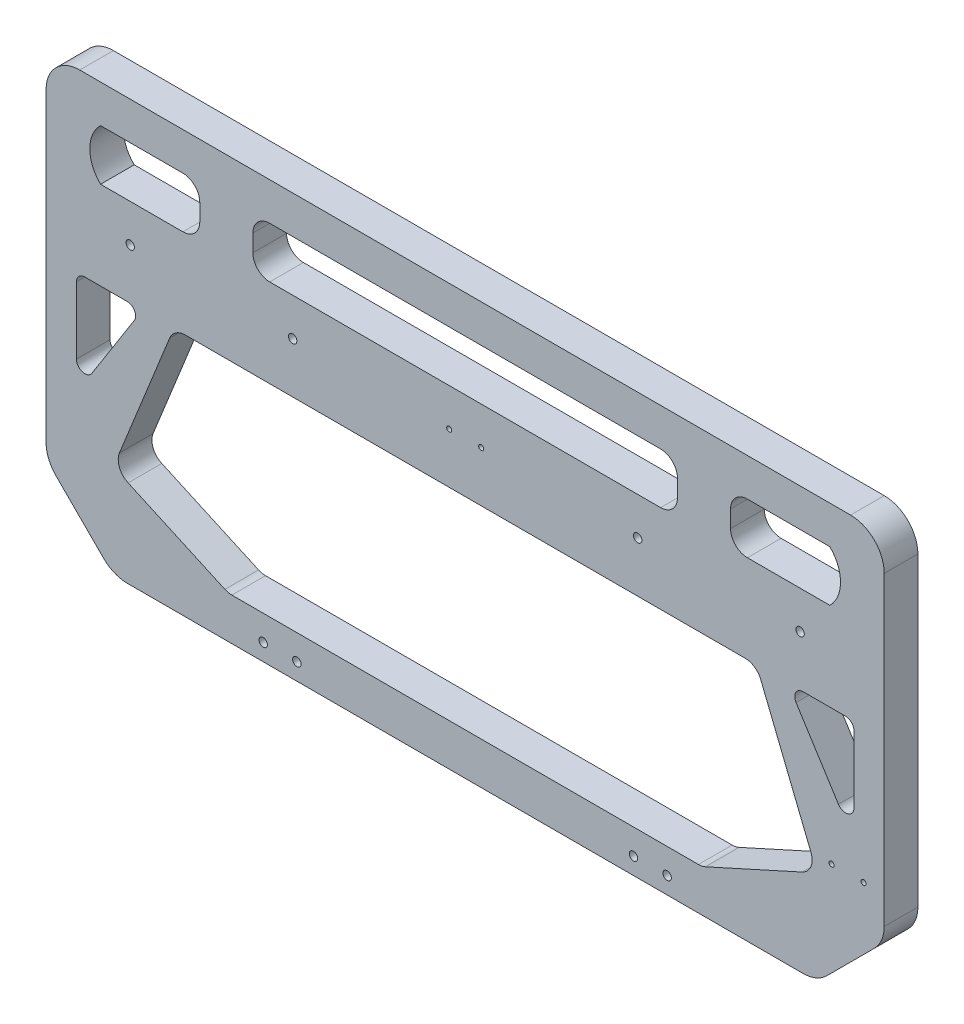
SolidWorks part; units mm, degrees
ref_plane "Ön Düzlem" through (0, 0, 0) normal (0, 0, 1) x (1, 0, 0)
ref_plane "Üst Düzlem" through (0, 0, 0) normal (0, 1, 0) x (1, 0, 0)
ref_plane "Sağ Düzlem" through (0, 0, 0) normal (1, 0, 0) x (0, 0, -1)
sketch "Sketch1" plane through (0, 0, 0) normal (0, 0, 1) x (1, 0, 0)
  line L0 (0, 125) -> (0, -125) construction
  line L1 (-200.7157, -125) -> (200.7157, -125)
  line L2 (-249, -76.7157) -> (-249, 105)
  line L3 (-229, 125) -> (229, 125)
  line L4 (249, -76.7157) -> (249, 105)
  line L5 (-249, 50) -> (249, 50) construction
  line L6 (116.1318, 102.5635) -> (-116.1318, 102.5635)
  line L7 (-126.1318, 92.5635) -> (-126.1318, 82.3895)
  line L8 (-116.1318, 72.3895) -> (116.1318, 72.3895)
  line L9 (-216.6539, 102.5635) -> (-167.6985, 102.5635)
  line L13 (-157.6985, 92.5635) -> (-157.6985, 82.3895)
  line L14 (-167.6985, 72.3895) -> (-216.6539, 72.3895)
  line L15 (166.3188, 20) -> (-166.3188, 20)
  line L16 (-175.5934, 13.7393) -> (-205.414, -60.224)
  line L17 (-200.2635, -73.0733) -> (-142.7494, -99.11)
  line L18 (-138.6253, -100) -> (138.6253, -100)
  line L19 (-231, 15) -> (-231, -24.7569)
  line L20 (-221.7756, -27.4317) -> (-196.6027, 12.3252)
  line L21 (-200.8271, 20) -> (-226, 20)
  line L22 (200.2635, -73.0733) -> (142.7494, -99.11)
  line L23 (175.5934, 13.7393) -> (205.414, -60.224)
  line L24 (126.1318, 92.5635) -> (126.1318, 82.3895)
  line L25 (221.7756, -27.4317) -> (196.6027, 12.3252)
  line L26 (231, 15) -> (231, -24.7569)
  line L27 (200.8271, 20) -> (226, 20)
  line L28 (157.6985, 92.5635) -> (157.6985, 82.3895)
  line L29 (216.6539, 102.5635) -> (167.6985, 102.5635)
  line L30 (167.6985, 72.3895) -> (216.6539, 72.3895)
  line L31 (-243.1421, -90.8579) -> (-214.8579, -119.1421)
  line L32 (214.8579, -119.1421) -> (243.1421, -90.8579)
  circle A0 centre (-199, 50) radius 2.5
  circle A1 centre (-102.5, 50) radius 2.5
  circle A2 centre (102.5, 50) radius 2.5
  circle A3 centre (199, 50) radius 2.5
  circle A4 centre (-9.5, 50) radius 1.5
  circle A5 centre (9.5, 50) radius 1.5
  arc A6 (-216.6539, 102.5635) -> (-216.6539, 72.3895) centre (-202.0042, 87.4765) ccw
  arc A7 (-167.6985, 102.5635) -> (-157.6985, 92.5635) centre (-167.6985, 92.5635) cw
  arc A8 (-157.6985, 82.3895) -> (-167.6985, 72.3895) centre (-167.6985, 82.3895) cw
  arc A9 (-116.1318, 102.5635) -> (-126.1318, 92.5635) centre (-116.1318, 92.5635) ccw
  arc A10 (-126.1318, 82.3895) -> (-116.1318, 72.3895) centre (-116.1318, 82.3895) ccw
  arc A11 (-231, -24.7569) -> (-221.7756, -27.4317) centre (-226, -24.7569) ccw
  arc A12 (-231, 15) -> (-226, 20) centre (-226, 15) cw
  arc A13 (-196.6027, 12.3252) -> (-200.8271, 20) centre (-200.8271, 15) ccw
  arc A14 (-166.3188, 20) -> (-175.5934, 13.7393) centre (-166.3188, 10) ccw
  arc A15 (-142.7494, -99.11) -> (-138.6253, -100) centre (-138.6253, -90) ccw
  arc A16 (-205.414, -60.224) -> (-200.2635, -73.0733) centre (-196.1394, -63.9633) ccw
  arc A17 (142.7494, -99.11) -> (138.6253, -100) centre (138.6253, -90) cw
  arc A18 (205.414, -60.224) -> (200.2635, -73.0733) centre (196.1394, -63.9633) cw
  arc A19 (166.3188, 20) -> (175.5934, 13.7393) centre (166.3188, 10) cw
  arc A20 (116.1318, 102.5635) -> (126.1318, 92.5635) centre (116.1318, 92.5635) cw
  arc A21 (126.1318, 82.3895) -> (116.1318, 72.3895) centre (116.1318, 82.3895) cw
  arc A22 (231, -24.7569) -> (221.7756, -27.4317) centre (226, -24.7569) cw
  arc A23 (231, 15) -> (226, 20) centre (226, 15) ccw
  arc A24 (196.6027, 12.3252) -> (200.8271, 20) centre (200.8271, 15) cw
  arc A25 (167.6985, 102.5635) -> (157.6985, 92.5635) centre (167.6985, 92.5635) ccw
  arc A26 (216.6539, 102.5635) -> (216.6539, 72.3895) centre (202.0042, 87.4765) cw
  arc A27 (157.6985, 82.3895) -> (167.6985, 72.3895) centre (167.6985, 82.3895) ccw
  arc A28 (229, 125) -> (249, 105) centre (229, 105) cw
  arc A29 (-249, 105) -> (-229, 125) centre (-229, 105) cw
  arc A30 (-243.1421, -90.8579) -> (-249, -76.7157) centre (-229, -76.7157) cw
  arc A31 (-214.8579, -119.1421) -> (-200.7157, -125) centre (-200.7157, -105) ccw
  arc A32 (214.8579, -119.1421) -> (200.7157, -125) centre (200.7157, -105) cw
  arc A33 (243.1421, -90.8579) -> (249, -76.7157) centre (229, -76.7157) ccw
  point P0 (0, 0)
  point P2 (-249, -125)
  point P4 (249, -125)
  point P59 (-209, -69.1183)
  point P63 (0, -100)
  point P69 (0, 20)
  point P73 (0, 102.5635)
  point P75 (0, 72.3895)
  point P99 (249, 125)
  point P104 (-249, -85)
  point P107 (-209, -125)
  point P110 (209, -125)
  point P113 (249, -85)
  dimension "D3" = 5
  dimension "D4" = 5
  dimension "D8" = 3
  dimension "D10" = 10
  dimension "D11" = 10
  dimension "D16" = 5
  dimension "D17" = 10
  dimension "D18" = 20
  dimension "D19" = 20
  dimension "D1" = 250
  dimension "D2" = 498
  dimension "D5" = 50
  dimension "D6" = 102.5
  dimension "D7" = 75
  dimension "D9" = 9.5
  dimension "D12" = 25
  dimension "D13" = 30
  dimension "D14" = 40
  dimension "D15" = 18
extrude "Boss-Extrude1" add sketch "Sketch1" along normal blind 20
sketch "Sketch3" plane through (0, 0, 20) normal (0, 0, 1) x (1, 0, 0)
  line L0 (0, 0) -> (0, -125) construction
  line L1 (-200.7157, -125) -> (200.7157, -125) construction
  line L3 (-74.5418, -125) -> (-74.5418, -105) construction
  line L4 (-74.5418, -115) -> (-10.3726, -115) construction
  circle A0 centre (-100, -115) radius 2.5
  circle A1 centre (-120, -115) radius 2.5
  circle A2 centre (100, -115) radius 2.5
  circle A3 centre (120, -115) radius 2.5
  dimension "D2" = 5
  dimension "D3" = 5
  dimension "D1" = 20
  dimension "D4" = 100
  dimension "D5" = 20
extrude "Cut-Extrude1" cut sketch "Sketch3" against normal up to surface (20 mm away) up to face at (196.5, 50, 0)
sketch "Sketch4" plane through (0, 0, 20) normal (0, 0, 1) x (1, 0, 0)
  line L0 (205.414, -60.224) -> (249, -60.224) construction
  line L1 (249, -76.7157) -> (249, 105) construction
  circle A0 centre (236.707, -60.224) radius 1.5
  circle A1 centre (217.707, -60.224) radius 1.5
  point P9 (227.207, -60.224)
  dimension "D1" = 3
  dimension "D2" = 3
  dimension "D3" = 9.5
  dimension "D4" = 19
extrude "Cut-Extrude2" cut sketch "Sketch4" against normal up to surface (20 mm away) up to face at (117.5, -115, 0)
